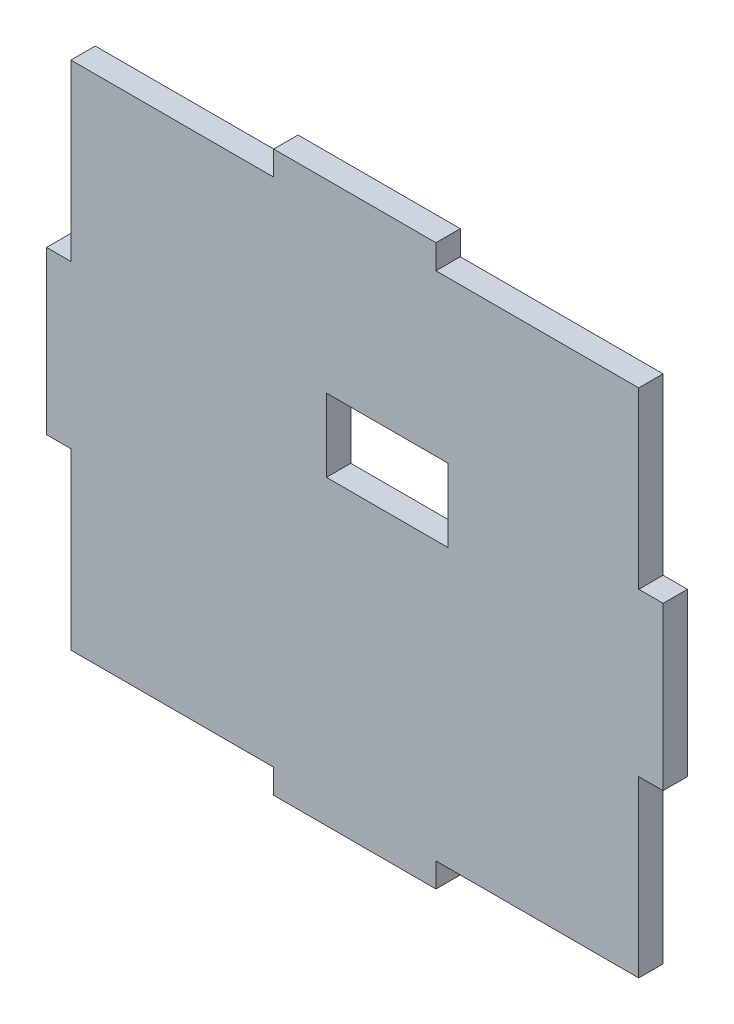
SolidWorks part; units mm, degrees
ref_plane "Front Plane" through (0, 0, 0) normal (0, 0, 1) x (1, 0, 0)
ref_plane "Top Plane" through (0, 0, 0) normal (0, 1, 0) x (1, 0, 0)
ref_plane "Right Plane" through (0, 0, 0) normal (1, 0, 0) x (0, 0, -1)
sketch "Sketch1" plane through (0, 0, 0) normal (0, 0, 1) x (1, 0, 0)
  line L1 (-35, 31.5) -> (35, 31.5)
  line L2 (-35, 31.5) -> (-35, -31.5)
  line L3 (-35, -31.5) -> (35, -31.5)
  line L4 (35, 31.5) -> (35, -31.5)
  line L5 (-35, 31.5) -> (35, -31.5) construction
  line L6 (-35, -31.5) -> (35, 31.5) construction
  point P0 (0, 0)
  dimension "D1" = 70
  dimension "D2" = 63
extrude "Boss-Extrude1" add sketch "Sketch1" along normal blind 3
sketch "Sketch2" plane through (0, 0, 3) normal (0, 0, 1) x (1, 0, 0)
  line L0 (-35, -31.5) -> (35, -31.5) construction
  line L1 (-3.5, 11.7) -> (11.5, 11.7)
  line L2 (-3.5, 11.7) -> (-3.5, 2.7)
  line L3 (-3.5, 2.7) -> (11.5, 2.7)
  line L4 (11.5, 11.7) -> (11.5, 2.7)
  line L5 (-3.5, 11.7) -> (11.5, 2.7) construction
  line L6 (-3.5, 2.7) -> (11.5, 11.7) construction
  line L7 (35, -31.5) -> (35, 31.5) construction
  point P0 (4, 7.2)
  dimension "D1" = 9
  dimension "D2" = 15
  dimension "D3" = 38.7
  dimension "D4" = 31
extrude "Cut-Extrude1" cut sketch "Sketch2" against normal blind 3
sketch "Sketch4" plane through (0, 0, 3) normal (0, 0, 1) x (1, 0, 0)
  line L0 (0, 0) -> (36.5, 0) construction
  line L1 (38, 10) -> (35, 10)
  line L2 (38, 10) -> (38, -10)
  line L3 (38, -10) -> (35, -10)
  line L4 (35, 10) -> (35, -10)
  line L5 (38, 10) -> (35, -10) construction
  line L6 (38, -10) -> (35, 10) construction
  line L7 (-35, 10) -> (-38, 10)
  line L8 (-35, 10) -> (-35, -10)
  line L9 (-35, -10) -> (-38, -10)
  line L10 (-38, 10) -> (-38, -10)
  line L11 (-35, 10) -> (-38, -10) construction
  line L12 (-35, -10) -> (-38, 10) construction
  line L13 (0, 0) -> (-36.5, 0) construction
  line L14 (-35, 31.5) -> (-35, -31.5) construction
  line L15 (35, -31.5) -> (35, 31.5) construction
  line L16 (0, -33) -> (0, 0) construction
  line L17 (10, 34.5) -> (-10, 34.5)
  line L18 (10, 34.5) -> (10, 31.5)
  line L19 (10, 31.5) -> (-10, 31.5)
  line L20 (-10, 34.5) -> (-10, 31.5)
  line L21 (10, 34.5) -> (-10, 31.5) construction
  line L22 (10, 31.5) -> (-10, 34.5) construction
  line L23 (10, -31.5) -> (-10, -31.5)
  line L24 (10, -31.5) -> (10, -34.5)
  line L25 (10, -34.5) -> (-10, -34.5)
  line L26 (-10, -31.5) -> (-10, -34.5)
  line L27 (10, -31.5) -> (-10, -34.5) construction
  line L28 (10, -34.5) -> (-10, -31.5) construction
  line L29 (0, 0) -> (0, 33) construction
  line L30 (-35, -31.5) -> (35, -31.5) construction
  line L31 (35, 31.5) -> (-35, 31.5) construction
  point P0 (36.5, 0)
  point P5 (-36.5, 0)
  point P18 (0, 33)
  point P23 (0, -33)
  dimension "D1" = 20
  dimension "D2" = 3
  dimension "D3" = 20
extrude "Boss-Extrude2" add sketch "Sketch4" against normal up to surface (3 mm away) up to face at (4, 7.2, 0)
